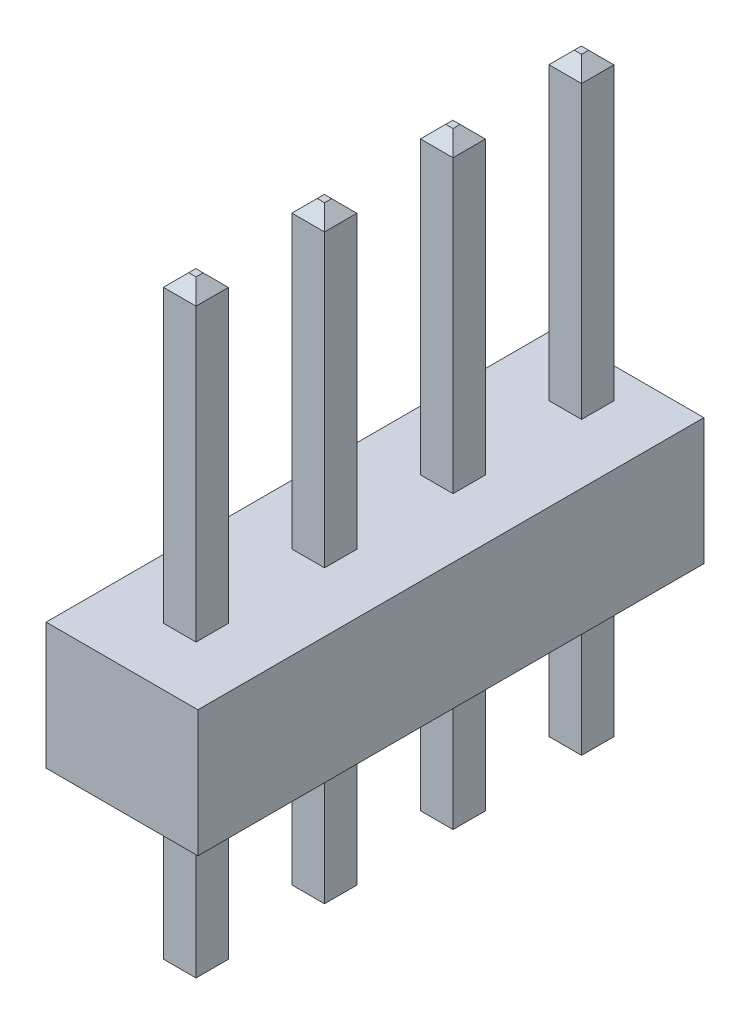
SolidWorks part; units mm, degrees
ref_plane "Front Plane" through (0, 0, 0) normal (0, 0, 1) x (1, 0, 0)
ref_plane "Top Plane" through (0, 0, 0) normal (0, 1, 0) x (1, 0, 0)
ref_plane "Right Plane" through (0, 0, 0) normal (1, 0, 0) x (0, 0, -1)
sketch "Sketch1" plane through (0, 0, 0) normal (0, 0, 1) x (1, 0, 0)
  line L0 (1.5, 0) -> (-1.5, 0) construction
  line L1 (-1.5, 1.25) -> (1.5, 1.25)
  line L2 (-1.5, 1.25) -> (-1.5, -1.25)
  line L3 (-1.5, -1.25) -> (1.5, -1.25)
  line L4 (1.5, 1.25) -> (1.5, -1.25)
  dimension "D1" = 3
  dimension "D2" = 2.5
extrude "Extrude1" add sketch "Sketch1" along normal mid plane 10
ref_plane "Plane4" through (0, 0, 3.86) normal (0, 0, 1) x (1, 0, 0)
sketch "Sketch2" plane through (0, 0, 3.86) normal (0, 0, 1) x (1, 0, 0)
  line L0 (-0.3225, 1.25) -> (-0.3225, 7.25)
  line L1 (1.5, 1.25) -> (-1.5, 1.25) construction
  line L2 (0.3225, 1.25) -> (0.3225, 7.25)
  line L3 (-0.3225, 1.25) -> (0.3225, 1.25)
  line L4 (0, 0) -> (0, 1.25) construction
  line L5 (0.3225, 7.25) -> (-0.3225, 7.25)
  line L6 (-6.5025, 2.4326) -> (-6.5025, 3.0683)
  line L8 (-0.3225, -1.25) -> (-0.3225, -4.75)
  line L9 (-1.5, -1.25) -> (1.5, -1.25) construction
  line L10 (-0.3225, -4.75) -> (0.3225, -4.75)
  line L11 (0.3225, -4.75) -> (0.3225, -1.25)
  line L12 (-0.3225, -1.25) -> (0.3225, -1.25)
  dimension "D1" = 0.645
  dimension "D2" = 6
  dimension "D8" = 3.5
extrude "Extrude2" add sketch "Sketch2" against normal blind 0.64 contours L2 L5 L0 L3 | L12 L8 L10 L11
pattern_linear "LPattern1" count 4 spacing 2.54 along (0, 0, -1) of "Extrude2"
chamfer "Chamfer1" distance 0.25 angle 45 32 edges at (0.3225, -4.75, 3.54) (-0.3225, -4.75, 3.54) (0.3225, -4.75, -1.54) (-0.3225, -4.75, -1.54) (0.3225, -4.75, 1) (-0.3225, -4.75, 1) (0.3225, -4.75, -4.08) (-0.3225, -4.75, -4.08) (0, -4.75, -4.4) (0, -4.75, -3.76) (0, -4.75, 3.22) (0, -4.75, 3.86) (0, -4.75, -1.86) (0, -4.75, -1.22) (0, -4.75, 0.68) (0, -4.75, 1.32) (-0.3225, 7.25, 3.54) (0, 7.25, 3.22) (0.3225, 7.25, 3.54) (0, 7.25, 3.86) (-0.3225, 7.25, 1) (0, 7.25, 0.68) (0.3225, 7.25, 1) (0, 7.25, 1.32) (-0.3225, 7.25, -1.54) (0, 7.25, -1.86) (0.3225, 7.25, -1.54) (0, 7.25, -1.22) (-0.3225, 7.25, -4.08) (0, 7.25, -4.4) (0.3225, 7.25, -4.08) (0, 7.25, -3.76)
